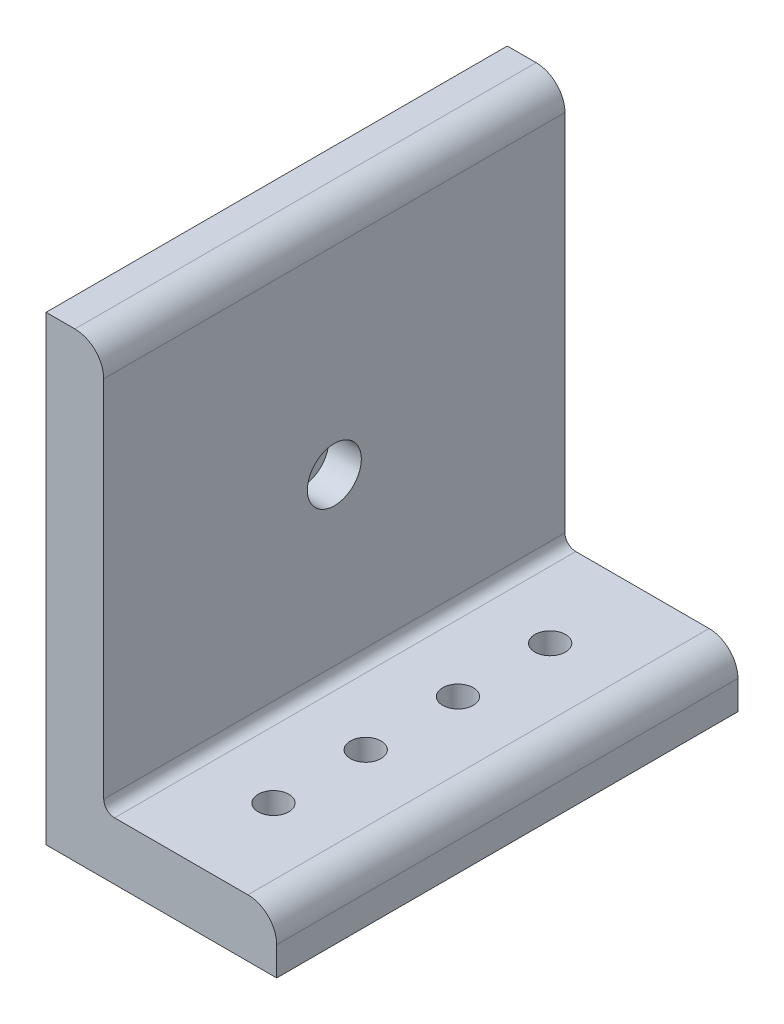
SolidWorks part; units mm, degrees
material "Plain Carbon Steel"
ref_plane "Front Plane" through (0, 0, 0) normal (0, 0, 1) x (1, 0, 0)
ref_plane "Top Plane" through (0, 0, 0) normal (0, 1, 0) x (1, 0, 0)
ref_plane "Right Plane" through (0, 0, 0) normal (1, 0, 0) x (0, 0, -1)
sketch3d "3DSketch1"
  line L0 (-396.6214, -221.175, -32.0639) -> (390.9374, -221.175, -32.0639) construction
  line L1 (390.9374, -221.175, -133.6639) -> (390.9374, -221.175, 69.5361)
  line L2 (517.7786, -227.525, 272.7361) -> (517.7786, -227.525, -336.8639) construction
  line L3 (-396.6214, -221.175, -32.0639) -> (-396.6214, -221.175, -336.8639) construction
  line L5 (-396.6214, -221.175, -32.0639) -> (-396.6214, -221.175, 272.7361) construction
  line L10 (-396.6214, -221.175, -336.8639) -> (-396.6214, -221.175, 272.7361) construction
  line L11 (-396.6214, -221.175, 272.7361) -> (517.7786, -221.175, 272.7361) construction
  point P5 (390.9374, -221.175, -32.0639)
  dimension "D1" = 127
  dimension "D2" = 203.2
other "L angle L8X4X1(1)"
ref_plane "Plane1" through (390.9374, -221.175, -133.6639) normal (0, 0, 1) x (1, 0, 0)
sketch "Sketch114" plane through (390.9374, -221.175, -133.6639) normal (0, 0, 1) x (1, 0, 0)
  line L0 (0, 0) -> (0, 203.2)
  line L1 (0, 203.2) -> (12.7051, 203.2)
  line L2 (25.4, 190.5051) -> (25.4, 30.1625)
  line L3 (30.1625, 25.4) -> (88.9051, 25.4)
  line L4 (101.6, 12.7051) -> (101.6, 0)
  line L5 (101.6, 0) -> (0, 0)
  arc A0 (101.6, 12.7051) -> (88.9051, 25.4) centre (88.9051, 12.7051) ccw
  arc A1 (12.7051, 203.2) -> (25.4, 190.5051) centre (12.7051, 190.5051) cw
  arc A2 (30.1625, 25.4) -> (25.4, 30.1625) centre (30.1625, 30.1625) cw
  circle A3 centre (0, 0) radius 12.7 construction
  point P10 (0, 101.6)
  point P14 (50.8, 0)
  point P15 (0, 0)
  dimension "D2" = 12.7051
  dimension "Radius_1" = 4.7625
  dimension "Radius_2" = 12.7
  dimension "D1" = 25.4
  dimension "V_leg" = 203.2
  dimension "H_leg" = 101.6
  dimension "Thickness" = 25.4
  dimension "Flat_wid" = 12.7051
sketch "Sketch115" plane through (0, -195.775, 0) normal (0, 1, 0) x (1, 0, 0)
  line L0 (421.0999, 133.6639) -> (479.8425, 133.6639) construction
  line L1 (450.4712, 133.6639) -> (450.4712, -69.5361) construction
  line L2 (479.8425, -69.5361) -> (421.0999, -69.5361) construction
  line L3 (450.4712, 133.6639) -> (450.4712, 93.0239)
  line L4 (450.4712, 93.0239) -> (450.4712, 52.3839)
  line L5 (450.4712, 52.3839) -> (450.4712, 11.7439)
  line L6 (450.4712, 11.7439) -> (450.4712, -28.8961)
  line L7 (450.4712, -28.8961) -> (450.4712, -69.5361)
  point P8 (450.4712, 93.0239)
  point P9 (450.4712, 52.3839)
  point P10 (450.4712, 11.7439)
  point P11 (450.4712, -28.8961)
hole_wizard "1/2 Clearance Hole1" positions "Sketch115" profile "Sketch116" hole size "1/2" standard "ANSI Inch" end condition up to next
sketch "Sketch116" plane through (450.4712, -195.775, 28.8961) normal (1, 0, 0) x (0, 0, 1)
  line L0 (0, 0) -> (0, 25.4)
  line L1 (0, 25.4) -> (6.7462, 25.4)
  line L2 (6.7462, 25.4) -> (6.7462, 0)
  line L5 (6.7462, 0) -> (0, 0)
  line L11 (0, -6.35) -> (0, 107.95) construction
  dimension "Thru Hole Dia." = 13.4925
  dimension "Thru Hole Depth" = 25.4
sketch "Sketch117" plane through (416.3374, 0, 0) normal (1, 0, 0) x (0, 0, -1)
  line L0 (32.0639, -30.6699) -> (32.0639, -118.0002) construction
  line L1 (-69.5361, -30.6699) -> (133.6639, -30.6699) construction
  line L2 (-69.5361, -221.175) -> (133.6639, -221.175) construction
  point P0 (32.0639, -118.0002)
  dimension "D1" = 103.1748
hole_wizard "CBORE for M12 Hex Head Bolt1" positions "Sketch117" profile "Sketch118" counterbore size "M12" standard "ANSI Metric" end condition through all
sketch "Sketch118" plane through (416.3374, -118.0002, -32.0639) normal (0, 1, 0) x (0, 0, -1)
  line L0 (0, 0) -> (0, 25.4)
  line L1 (0, 25.4) -> (6.75, 25.4)
  line L3 (6.75, 25.4) -> (6.75, 14.3)
  line L4 (6.75, 14.3) -> (11.89, 14.3)
  line L5 (11.89, 14.3) -> (11.89, 0)
  line L7 (11.89, 0) -> (0, 0)
  line L11 (0, -6.35) -> (0, 107.95) construction
  dimension "Thru Hole Dia." = 13.5
  dimension "Thru Hole Depth" = 25.4
  dimension "C'Bore Dia." = 23.78
  dimension "C'Bore Depth" = 14.3
